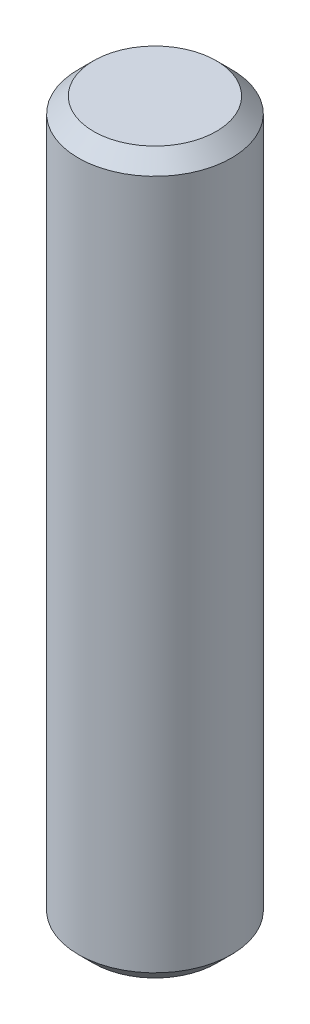
SolidWorks part; units mm, degrees
material "Commercially Pure titanium (Ti-55)  UNS R50550*"
ref_plane "Front Plane" through (0, 0, 0) normal (0, 0, 1) x (1, 0, 0)
ref_plane "Top Plane" through (0, 0, 0) normal (0, 1, 0) x (1, 0, 0)
ref_plane "Right Plane" through (0, 0, 0) normal (1, 0, 0) x (0, 0, -1)
sketch "Sketch1" plane through (0, 0, 0) normal (0, 1, 0) x (1, 0, 0)
  circle A0 centre (0, 0) radius 0.5
  dimension "D1" = 1
extrude "Boss-Extrude1" add sketch "Sketch1" along normal blind 4.7
chamfer "Chamfer1" distance 0.1 angle 45 2 edges at (0, 0, 0.5) (0, 4.7, 0.5)
